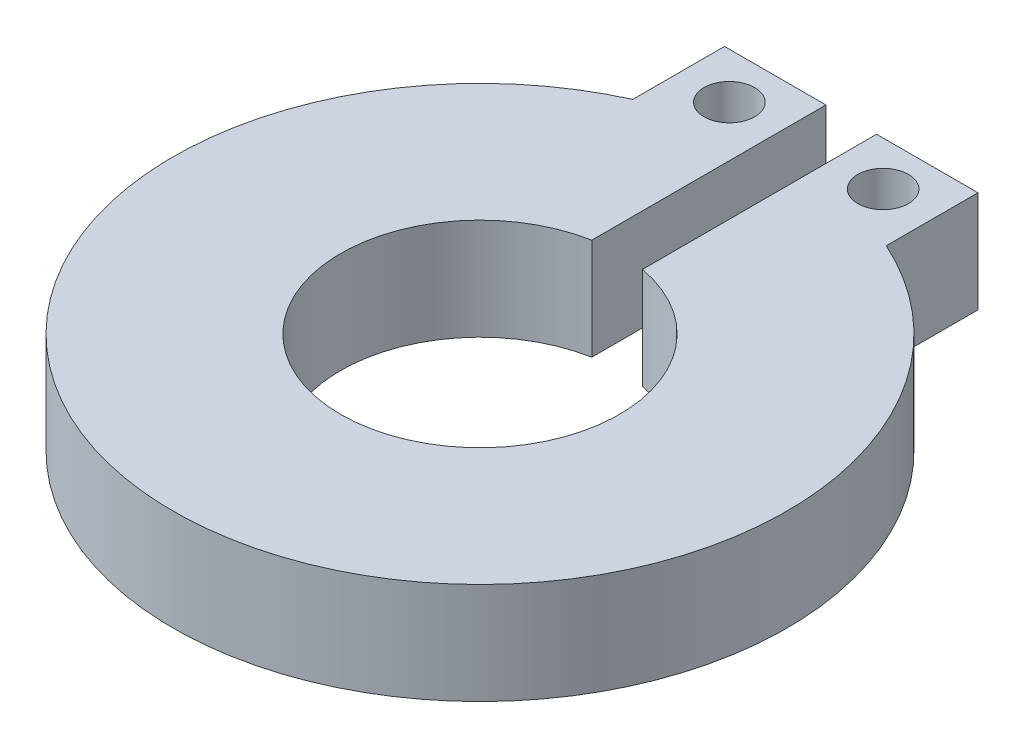
SolidWorks part; units mm, degrees
ref_plane "Ön Düzlem" through (0, 0, 0) normal (0, 0, 1) x (1, 0, 0)
ref_plane "Üst Düzlem" through (0, 0, 0) normal (0, 1, 0) x (1, 0, 0)
ref_plane "Sağ Düzlem" through (0, 0, 0) normal (1, 0, 0) x (0, 0, -1)
sketch "Çizim1" plane through (0, 0, 0) normal (0, 1, 0) x (1, 0, 0)
  line L2 (1, 5.4083) -> (1, 14.6457)
  line L4 (-1, 5.4083) -> (-1, 14.6457)
  line L7 (-1, 14.6457) -> (-5, 14.6457)
  line L8 (-1, 14.6457) -> (-1, 9.023)
  line L10 (-5, 14.6457) -> (-5, 11.0261)
  line L11 (1, 14.6457) -> (5, 14.6457)
  line L12 (1, 14.6457) -> (1, 9.023)
  line L14 (5, 14.6457) -> (5, 11.0261)
  arc A0 (-1, 5.4083) -> (1, 5.4083) centre (0, 0) ccw
  arc A2 (-5, 11.0261) -> (5, 11.0261) centre (0, 0) ccw
  circle A3 centre (-3, 12.8359) radius 1
  circle A4 centre (3, 12.9031) radius 1
  point P4 (0, 5.5)
  dimension "D1" = 11
  dimension "D2" = 2
  dimension "D4" = 2
  dimension "D3" = 2
  dimension "D5" = 4
  dimension "D6" = 4
  dimension "D7" = 6
  dimension "D8" = 2
  dimension "D9" = 2
extrude "Yükseklik-Ekstrüzyon1" add sketch "Çizim1" along normal blind 4 contours L10 A2 L14 L11 L2 A0 L4 L7 A4 A3
